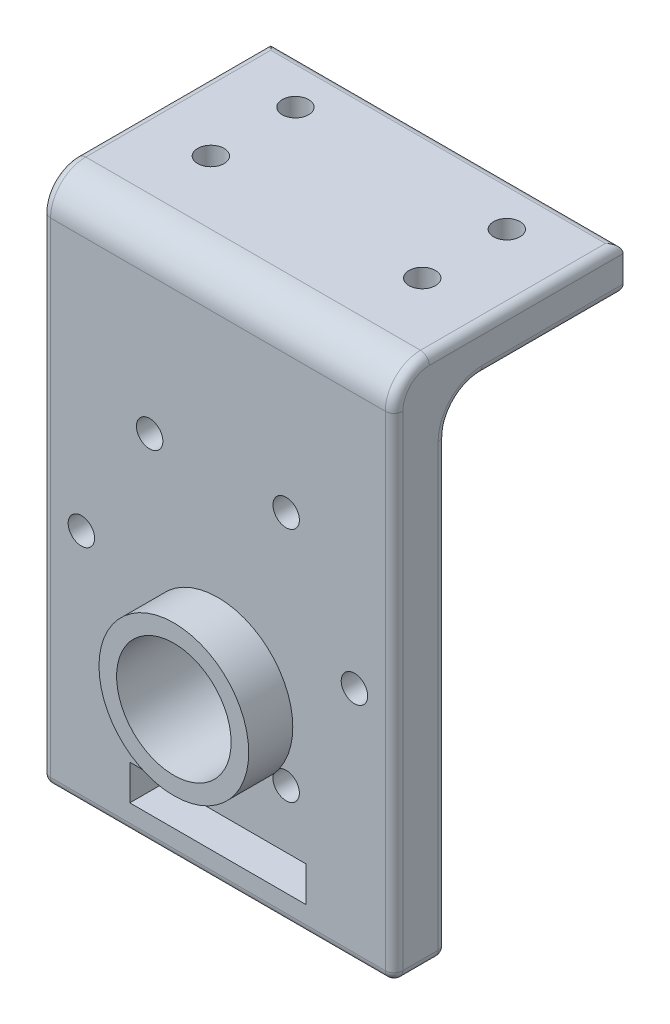
SolidWorks part; units mm, degrees
ref_plane "前视基准面" through (0, 0, 0) normal (0, 0, 1) x (1, 0, 0)
ref_plane "上视基准面" through (0, 0, 0) normal (0, 1, 0) x (1, 0, 0)
ref_plane "右视基准面" through (0, 0, 0) normal (1, 0, 0) x (0, 0, -1)
other "Configuration Table"
sketch "草图1" plane through (0, 0, 0) normal (0, 0, 1) x (1, 0, 0)
  line L1 (0, 0) -> (40, 0)
  line L2 (0, 0) -> (0, -60)
  line L3 (0, -60) -> (40, -60)
  line L4 (40, 0) -> (40, -60)
  dimension "D1" = 40
  dimension "D2" = 60
extrude "凸台-拉伸1" add sketch "草图1" along normal blind 6
sketch "草图2" plane through (0, 0, 0) normal (0, 0, -1) x (-1, 0, 0)
  line L0 (0, 0) -> (0, -60) construction
  line L1 (-40, 0) -> (0, 0)
  line L2 (-40, 0) -> (-40, -5)
  line L3 (-40, -5) -> (0, -5)
  line L4 (0, 0) -> (0, -5)
  dimension "D1" = 5
extrude "凸台-拉伸2" add sketch "草图2" along normal blind 20
sketch "草图3" plane through (0, 0, 6) normal (0, 0, 1) x (1, 0, 0)
  line L0 (0, 0) -> (0, -60) construction
  line L1 (0, -13) -> (40, -13)
  line L2 (0, -13) -> (0, -53)
  line L3 (0, -53) -> (40, -53)
  line L4 (40, -13) -> (40, -53)
  line L5 (40, -60) -> (40, 0) construction
  line L6 (40, 0) -> (0, 0) construction
  line L7 (0, -53) -> (40, -13)
  line L8 (40, -53) -> (0, -13)
  line L9 (20, -33) -> (40, -33)
  line L10 (20, -13) -> (20, -53)
  circle A0 centre (20, -33) radius 15.5
  circle A2 centre (35.5, -33) radius 1.5
  circle A3 centre (27.75, -46.4234) radius 1.5
  circle A4 centre (12.25, -46.4234) radius 1.5
  circle A5 centre (4.5, -33) radius 1.5
  circle A6 centre (12.25, -19.5766) radius 1.5
  circle A7 centre (27.75, -19.5766) radius 1.5
  circle A8 centre (20, -33) radius 18.3
  circle A9 centre (20, -40.3) radius 7.5
  point P15 (20, -33)
  point P16 (35.5, -33)
  point P32 (20, -51.3)
  dimension "D3" = 31
  dimension "D4" = 3
  dimension "D5" = 6
  dimension "D7" = 36.6
  dimension "D8" = 15
  dimension "D1" = 13
  dimension "D2" = 40
  dimension "D6" = 11
extrude "切除-拉伸1" cut sketch "草图3" against normal blind 20 contours A0 A3 | A0 A3 | L9 A2 A0 | A0 A2 L9 | L9 A2 A0 | A0 A2 L9 | A0 A7 | A0 A7 | A0 A6 | A0 A6 | A0 A5 | A0 A5 | A0 A4 | A0 A4
sketch "草图5" plane through (0, 0, 6) normal (0, 0, 1) x (1, 0, 0)
  circle A0 centre (20, -40.3) radius 8.5
  dimension "D1" = 17
extrude "凸台-拉伸3" add sketch "草图5" along normal blind 5
sketch "草图7" plane through (0, 0, 11) normal (0, 0, 1) x (1, 0, 0)
  circle A0 centre (20, -40.3) radius 6.5
  dimension "D1" = 13
extrude "切除-拉伸3" cut sketch "草图7" against normal blind 27
sketch "草图8" plane through (0, 0, 0) normal (0, 1, 0) x (1, 0, 0)
  line L2 (0, 20) -> (40, -6)
  line L3 (0, 10) -> (40, 10)
  line L5 (0, 0) -> (40, 0)
  line L6 (0, 0) -> (0, 20)
  line L7 (0, 20) -> (40, 20)
  line L8 (40, 0) -> (40, 20)
  line L9 (20, 0) -> (20, 20)
  circle A0 centre (8, 14.8) radius 1.5
  circle A1 centre (32, 14.8) radius 1.5
  circle A2 centre (32, 5.2) radius 1.5
  circle A3 centre (8, 5.2) radius 1.5
  point P16 (20, 7)
  dimension "D1" = 3
  dimension "D2" = 8
extrude "切除-拉伸5" cut sketch "草图8" against normal blind 27 contours L2 A0 | A3 | A1 | A2
sketch "草图9" plane through (0, 0, 0) normal (0, 0, -1) x (-1, 0, 0)
  line L1 (-30, -53) -> (-10, -53)
  line L2 (-30, -53) -> (-30, -57)
  line L3 (-30, -57) -> (-10, -57)
  line L4 (-10, -53) -> (-10, -57)
  line L5 (0, -60) -> (-40, -60) construction
  line L6 (0, -5) -> (0, -60) construction
  line L7 (-40, -60) -> (-40, -5) construction
  dimension "D1" = 3
  dimension "D2" = 10
  dimension "D3" = 10
  dimension "D4" = 4
extrude "切除-拉伸6" cut sketch "草图9" against normal blind 27
fillet "圆角1" radius 4 2 edges at (20, -5, 0) (20, 0, 6)
fillet "圆角2" radius 1 18 edges at (0, -34.5, 0) (0, -6.1716, -1.1716) (0, -32, 6) (0, -1.1716, 4.8284) (40, -34.5, 0) (40, -6.1716, -1.1716) (40, -32, 6) (40, -1.1716, 4.8284) (0, -60, 3) (20, -60, 6) (40, -60, 3) (20, -60, 0) (0, -5, -12) (0, 0, -9) (20, 0, -20) (20, -5, -20) (40, -5, -12) (40, 0, -9)
sketch "草图6" plane through (0, 0, 11) normal (0, 0, 1) x (1, 0, 0)
  circle A0 centre (20, -40.3) radius 6.5
  dimension "D1" = 13
